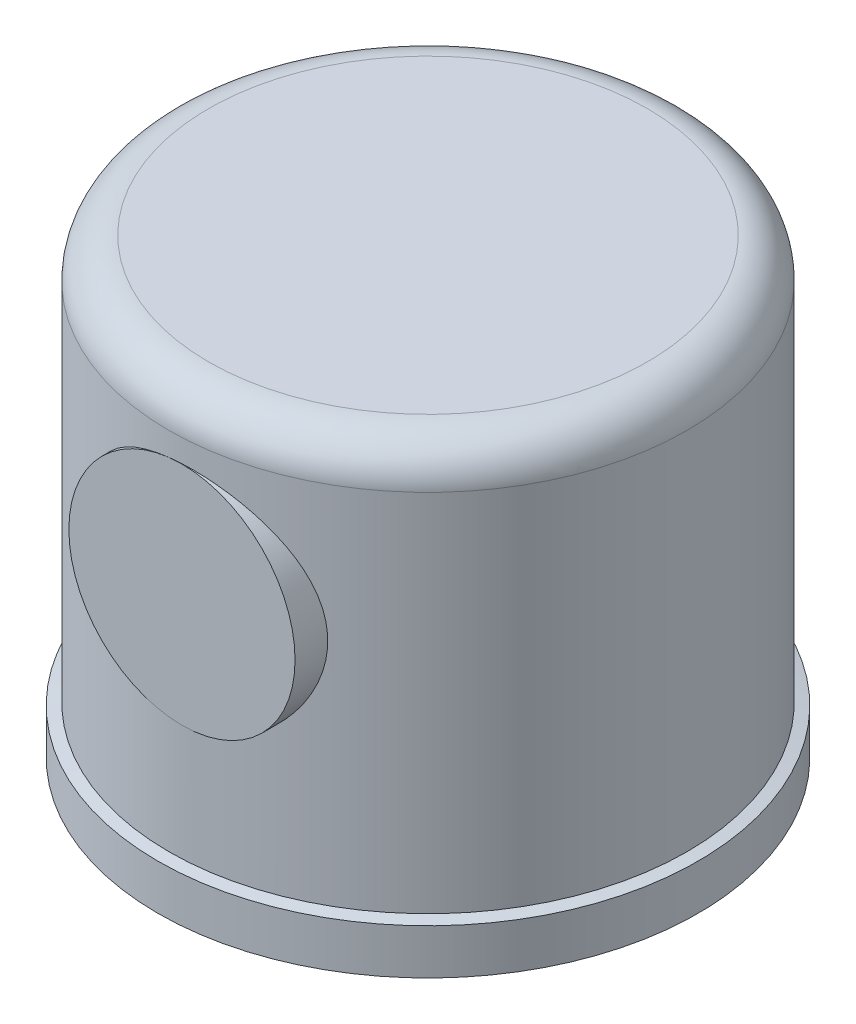
SolidWorks part; units mm, degrees
ref_plane "Front Plane" through (0, 0, 0) normal (0, 0, 1) x (1, 0, 0)
ref_plane "Top Plane" through (0, 0, 0) normal (0, 1, 0) x (1, 0, 0)
ref_plane "Right Plane" through (0, 0, 0) normal (1, 0, 0) x (0, 0, -1)
sketch "Sketch1" plane through (0, 0, 0) normal (0, 0, 1) x (1, 0, 0)
  line L0 (0, -0.7241) -> (0, 49.8133) construction
  line L1 (20.9, 0) -> (23.8716, 0)
  line L2 (23.8716, 0) -> (23.8716, 4)
  line L3 (23.8716, 4) -> (22.9, 4.2367)
  line L4 (22.9, 4.2367) -> (22.9, 36.5)
  line L5 (19.4, 40) -> (0, 40)
  line L6 (20.9, 0) -> (20.9, 11.9082)
  line L7 (18.9, 38) -> (0, 38)
  line L8 (0, 38) -> (0, 40)
  line L9 (20.9, 13.9082) -> (20.9, 36)
  line L10 (20.9, 13.9082) -> (0, 13.9082)
  line L12 (20.9, 11.9082) -> (0, 11.9082)
  line L13 (0, 13.9082) -> (0, 11.9082)
  arc A0 (22.9, 36.5) -> (19.4, 40) centre (19.4, 36.5) ccw
  arc A1 (20.9, 36) -> (18.9, 38) centre (18.9, 36) ccw
  point P11 (22.9, 40)
  dimension "D8" = 3.5
  dimension "D9" = 2
  dimension "D1" = 2
  dimension "D2" = 4
  dimension "D3" = 1
  dimension "D4" = 40
  dimension "D5" = 22.9
  dimension "D6" = 2
  dimension "D7" = 2.9716
  dimension "D10" = 2
revolve "Revolve1" add sketch "Sketch1" angle 360 about L0
ref_plane "Plane1" through (0, 4, 0) normal (0, 1, 0) x (1, 0, 0)
sketch "Sketch3" plane through (0, 0, 0) normal (0, 0, 1) x (1, 0, 0)
  point P0 (1.2404, 19.1989)
ref_point "Point1"
ref_plane "Plane2" through (0, 0, 22.9) normal (0, 0, 1) x (1, 0, 0)
sketch "Sketch4" plane through (0, 0, 22.9) normal (0, 0, 1) x (1, 0, 0)
  line L0 (22.9, 36.5) -> (-22.9, 36.5) construction
  circle A1 centre (1.1446, 24.5) radius 10
  dimension "D1" = 20
  dimension "D2" = 12
extrude "Boss-Extrude2" add sketch "Sketch4" against normal blind 6
ref_plane "Plane3" through (0, 0, 16.9) normal (0, 0, -1) x (-1, 0, 0)
